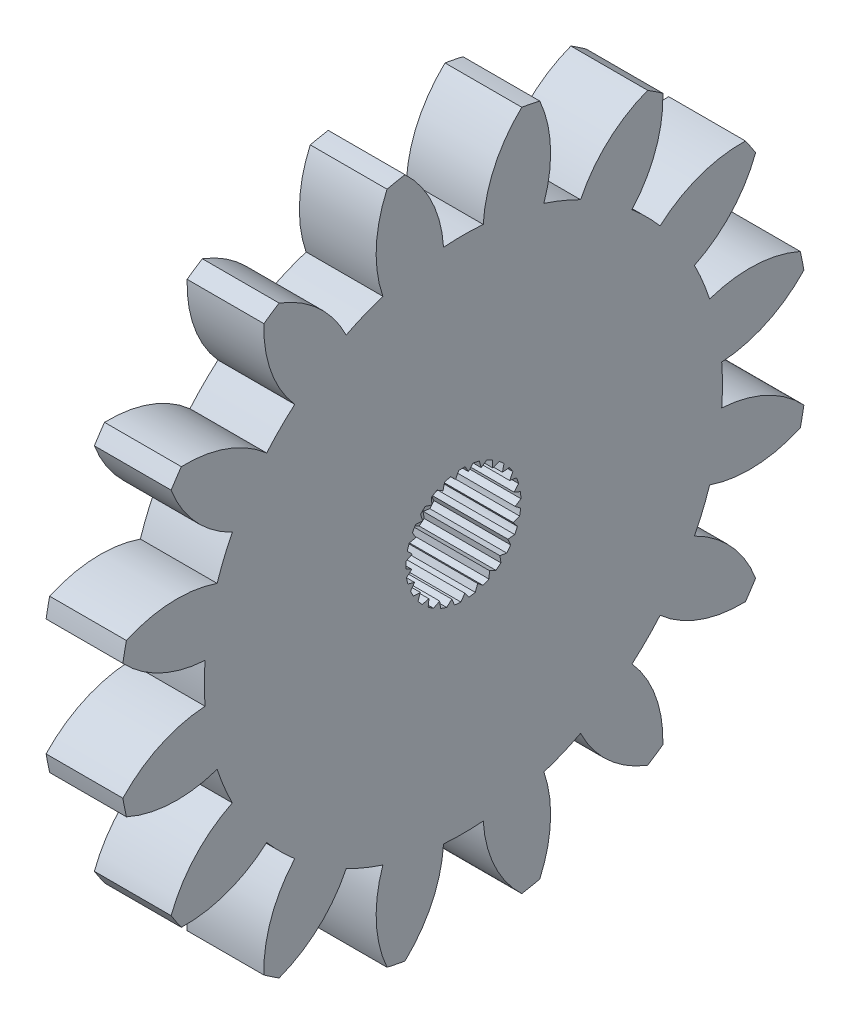
SolidWorks part; units mm, degrees
ref_plane "Plane1" through (0, 0, 0) normal (0, 0, 1) x (1, 0, 0)
ref_plane "Plane2" through (0, 0, 0) normal (0, 1, 0) x (1, 0, 0)
ref_plane "Plane3" through (0, 0, 0) normal (1, 0, 0) x (0, 0, -1)
other "Configuration Table"
sketch "HoldingSke" plane through (0, 0, 0) normal (0, 1, 0) x (1, 0, 0)
  line L0 (0, 0) -> (0.4806, -0.1378)
  line L1 (-15, 0) -> (100, 0) construction
  line L2 (0, 0) -> (-2.1039, 2.3779)
  line L3 (0, 0) -> (-11.863, 4.5341)
  line L4 (0, 0) -> (8.3015, 2.3804)
  line L5 (0, 0) -> (-46.8476, -17.4728)
  line L6 (0, 0) -> (-3.3159, -2.2372)
  line L7 (-2.1039, 2.3779) -> (8.6586, 51.2059)
  line L8 (-76.2, 54.61) -> (-75.2, 54.61)
  line L9 (-71.009, 38.7566) -> (-53.1078, 45.2721)
  line L10 (-76.2, 71.12) -> (104.1128, 71.12)
  line L11 (0, 0) -> (-4, 0)
  line L12 (-76.2, 101.6) -> (-76.133, 101.6)
  line L13 (24.9733, 27.94) -> (52.9518, 28.4284)
  line L14 (24.9733, 27.94) -> (24.9743, 27.94)
  line L15 (24.9733, 27.94) -> (100.4006, 29.5858)
  line L16 (-63.627, -2) -> (-12.827, -2)
  circle A0 centre (0, 0) radius 3
  circle A1 centre (0, 0) radius 13.499
  circle A2 centre (0, 0) radius 37.5
  circle A3 centre (0, 0) radius 3
  dimension "MHD" = 26.998
  dimension "Hub_dia" = 75
  dimension "Bore" = 6
  dimension "MBD" = 6
  dimension "Num_teeth" = 16
  dimension "Pitch" = 0.5
  dimension "Overall_len" = 50
  dimension "Show_teeth" = 16
  dimension "Thickness" = 4
  dimension "OAL" = 50.0001
  dimension "T_dim" = 1
  dimension "Ap" = 20
  dimension "H" = 19.05
  dimension "Pitch_radius" = 180.3128
  dimension "Width" = 4
  dimension "Backlash" = 0.067
  dimension "Addendum_fac" = 1
  dimension "Dedendum_fac" = 1.25
  dimension "Clearance_fac" = 0.25
  dimension "Dedendum_add" = 0.001
  dimension "Module" = 2
sketch "BasProSke" plane through (0, 0, 0) normal (0, 1, 0) x (1, 0, 0)
  line L0 (-10, 0) -> (60, 0) construction
  line L1 (0, 0) -> (0, 18)
  line L2 (0, 0) -> (4, 0)
  line L3 (4, 0) -> (4, 18)
  line L4 (4, 18) -> (0, 18)
  dimension "Thickness" = 4
  dimension "Diameter" = 36
revolve "Base-Revolve" add sketch "BasProSke" angle 360 about L0
sketch "TooCutSke" plane through (0, 0, 0) normal (1, 0, 0) x (0, 0, -1)
  line L1 (0, 0) -> (0, 107) construction
  line L2 (0, 0) -> (-1.6854, 15.911) construction
  line L3 (0, 0) -> (-6.2172, 31.2558) construction
  line L4 (-1.6854, 15.911) -> (-3.1086, 15.6279) construction
  arc A0 (1.0343, 13.4593) -> (-1.0343, 13.4593) centre (0, 0) ccw
  arc A1 (3.0657, 17.7628) -> (-3.0657, 17.7628) centre (0, 0) ccw
  circle A2 centre (0, 0) radius 16 construction
  circle A3 centre (0, 0) radius 15.0351 construction
  arc A4 (-1.0343, 13.4593) -> (-3.0657, 17.7628) centre (-7.4228, 13.075) ccw
  arc A5 (3.0657, 17.7628) -> (1.0343, 13.4593) centre (7.4228, 13.075) ccw
  dimension "Root_dia" = 26.998
  dimension "Overcut_dia" = 36.0508
  dimension "Pitch_dia" = 32
  dimension "Base_dia" = 30.0702
  dimension "Flank_rad" = 6.4
  dimension "Half_ang" = 11.25
  dimension "Half_CT" = 1.451
extrude "ToothCut" cut sketch "TooCutSke" along normal through all
fillet "Breaks" [suppressed] radius 0.04
fillet "RootFillets" [suppressed] radius 0.501
pattern_circular "TeethCuts" count 16 every 22.5 about axis through (-10, 0, 0) along (1, 0, 0) of "ToothCut", "RootFillets", "Breaks"
sketch "HubNeaOneSke" plane through (0, 0, 0) normal (-1, 0, 0) x (0, 0, 1)
  circle A0 centre (0, 0) radius 13.499
  dimension "Diameter" = 26.998
extrude "HubNearOne" [suppressed] add sketch "HubNeaOneSke" along normal blind 46.0001
sketch "HubNeaBotSke" plane through (0, 0, 0) normal (-1, 0, 0) x (0, 0, 1)
  circle A0 centre (0, 0) radius 13.499
  dimension "Diameter" = 26.998
extrude "HubNearBoth" [suppressed] add sketch "HubNeaBotSke" along normal blind 23
ref_plane "FarPln" through (4, 0, 0) normal (1, 0, 0) x (0, 0, -1)
sketch "HubFarSke" plane through (4, 0, 0) normal (1, 0, 0) x (0, 0, -1)
  circle A0 centre (0, 0) radius 13.499
  dimension "Diameter" = 26.998
extrude "HubFar" [suppressed] add sketch "HubFarSke" along normal blind 23
sketch "BorSke" plane through (0, 0, 0) normal (1, 0, 0) x (0, 0, -1)
  circle A0 centre (0, 0) radius 3
  dimension "Diameter" = 6
extrude "Bore" cut sketch "BorSke" along normal mid plane 100.0001
sketch "KeySke" plane through (0, 0, 0) normal (1, 0, 0) x (0, 0, -1)
  line L0 (-1, 0) -> (-1, 4)
  line L1 (-1, 4) -> (1, 4)
  line L2 (1, 4) -> (1, 0)
  line L3 (0, 0) -> (0, 34) construction
  line L4 (-1, 0) -> (1, 0)
  dimension "Offset" = 4
  dimension "Width" = 2
extrude "Keyway" [suppressed] cut sketch "KeySke" along normal mid plane 100.0001
pattern_circular "Keyway2" [suppressed] count 2 every 90 about axis through (-10, 0, 0) along (1, 0, 0)
sketch "Croquis4" plane through (0, 0, 0) normal (-1, 0, 0) x (0, 0, 1)
  line L0 (-0.2665, 2.6868) -> (-0.504, 2.9574)
  line L1 (-0.2665, 2.6868) -> (-0.0868, 2.9987)
  arc A1 (-0.0868, 2.9987) -> (-0.504, 2.9574) centre (0, 0) ccw
  dimension "D1" = 1.1212
  dimension "D2" = 6
  dimension "D3" = 0.36
  dimension "D4" = 1.3009
extrude "Saliente-Extruir2" add sketch "Croquis4" against normal through all
pattern_circular "MatrizC1" count 25 over 360 about axis through (0, 0, 0) along (1, 0, 0) of "Saliente-Extruir2"
sketch "Croquis5" plane through (0, 0, 0) normal (-1, 0, 0) x (0, 0, 1)
  circle A0 centre (0, 0) radius 1.5
  circle A1 centre (0, 0) radius 4
  dimension "D1" = 3
  dimension "D2" = 8
extrude "Saliente-Extruir3" add sketch "Croquis5" along normal blind 2 contours A1 A0
sketch "Croquis6" plane through (-2, 0, 0) normal (-1, 0, 0) x (0, 0, 1)
  circle A0 centre (0, 0) radius 2.85
  dimension "D1" = 5.7
extrude "Cortar-Extruir4" cut sketch "Croquis6" against normal blind 0.8
equation "' \"Module@HoldingSke\" = 6.35"
equation "' \"Num_teeth@HoldingSke\" = 12"
equation "' \"Ap@HoldingSke\" =  20"
equation "' \"Ap@HoldingSke\" = 20"
equation "' \"Width@HoldingSke\" = 0.5 * 25.4"
equation "' \"Hub_dia@HoldingSke\"= 1 * 25.4"
equation "' \"Hub_dia@HoldingSke\" = 1 * 25.4"
equation "' \"Overall_len@HoldingSke\" = 1.0 * 25.4"
equation "' \"Bore@HoldingSke\" = 0.75 * 25.4"
equation "' \"T_dim@HoldingSke\" = 0.1 * 25.4"
equation "' \"Width@KeySke\" = 0.25 * 25.4"
equation "' \"Show_teeth@HoldingSke\" = 13"
equation "' \"Backlash@HoldingSke\" = 0.009 * 25.4"
equation "' \"Addendum_fac@HoldingSke\" = 1.0"
equation "' \"Dedendum_fac@HoldingSke\" = 1.25"
equation "' \"Dedendum_add@HoldingSke\" = 0.00005 * 25.4"
equation "' \"Clearance_fac@HoldingSke\" = 0.25"
equation "\"Pitch@HoldingSke\" = 1 / \"Module@HoldingSke\""
equation "\"Overcut_dia@TooCutSke\" = (\"Num_teeth@HoldingSke\" + 2 * \"Addendum_fac@HoldingSke\") / \"Pitch@HoldingSke\" + 0.002 * 25.4"
equation "\"Pitch_dia@TooCutSke\" = \"Num_teeth@HoldingSke\" / \"Pitch@HoldingSke\""
equation "\"Base_dia@TooCutSke\" = \"Num_teeth@HoldingSke\" / \"Pitch@HoldingSke\" * cos((\"Ap@HoldingSke\"  * 3.14159265 / 180))"
equation "\"Root_dia@TooCutSke\" = (\"Num_teeth@HoldingSke\" + 2) / \"Pitch@HoldingSke\" - 2 * (\"Addendum_fac@HoldingSke\" + \"Dedendum_fac@HoldingSke\") / \"Pitch@HoldingSke\" - \"Dedendum_add@HoldingSke\" * 2"
equation "\"Half_ang@TooCutSke\" = 180 / \"Num_teeth@HoldingSke\""
equation "\"Half_CT@TooCutSke\" = \"Num_teeth@HoldingSke\" / \"Pitch@HoldingSke\" * sin((3.14159265 / 2 / \"Num_teeth@HoldingSke\")) / 2 - 7 * \"Backlash@HoldingSke\" / 4"
equation "\"Flank_rad@TooCutSke\" = \"Num_teeth@HoldingSke\" / \"Pitch@HoldingSke\" / 5"
equation "\"Radius@RootFillets\" = \"Clearance_fac@HoldingSke\" / \"Pitch@HoldingSke\" + \"Dedendum_add@HoldingSke\""
equation "\"Break_rad@Breaks\" = 0.02 / \"Pitch@HoldingSke\""
equation "\"Thickness@HoldingSke\" = \"Width@HoldingSke\""
equation "\"OAL@HoldingSke\" = \"Thickness@HoldingSke\""
equation "\"MHD@HoldingSke\" = (\"Num_teeth@HoldingSke\" + 2) / \"Pitch@HoldingSke\" - 2 * (\"Addendum_fac@HoldingSke\" + \"Dedendum_fac@HoldingSke\")  / \"Pitch@HoldingSke\" - \"Dedendum_add@HoldingSke\" * 2"
equation "\"MBD@HoldingSke\" = (\"Num_teeth@HoldingSke\" + 2) / \"Pitch@HoldingSke\" - 2 * (\"Addendum_fac@HoldingSke\" + \"Dedendum_fac@HoldingSke\")  / \"Pitch@HoldingSke\" - \"Dedendum_add@HoldingSke\" * 2 - 0.002 * 25.4"
equation "\"MHD@HoldingSke\" = ((sgn( \"MHD@HoldingSke\" - \"Hub_dia@HoldingSke\" )-1)*( \"MHD@HoldingSke\" - \"Hub_dia@HoldingSke\" ))/-2+ \"Hub_dia@HoldingSke\""
equation "\"MBD@HoldingSke\" = ((sgn( \"MBD@HoldingSke\" - \"Bore@HoldingSke\" )-1)*( \"MBD@HoldingSke\" - \"Bore@HoldingSke\" ))/-2+ \"Bore@HoldingSke\""
equation "\"OAL@HoldingSke\" = ((sgn( \"OAL@HoldingSke\" - \"Overall_len@HoldingSke\" )+1)*( \"OAL@HoldingSke\" - \"Overall_len@HoldingSke\" ))/2 + \"Overall_len@HoldingSke\" + 0.000002 * 25.4"
equation "\"Num_teeth@TeethCuts\" = int( \"Show_teeth@HoldingSke\" ) + 1"
equation "\"Num_teeth@TeethCuts\" = ((sgn( \"Num_teeth@TeethCuts\" - \"Num_teeth@HoldingSke\" )-1)*( \"Num_teeth@TeethCuts\" - \"Num_teeth@HoldingSke\" ))/-2+ \"Num_teeth@HoldingSke\""
equation "\"Num_teeth@TeethCuts\" = ((sgn( \"Num_teeth@TeethCuts\" - 2.0)+1)*( \"Num_teeth@TeethCuts\" - 2.0))/2 +2.0"
equation "\"Angle@TeethCuts\" = 360.0 / \"Num_teeth@HoldingSke\""
equation "\"Diameter@BasProSke\" = (\"Num_teeth@HoldingSke\" + 2 * \"Addendum_fac@HoldingSke\") / \"Pitch@HoldingSke\""
equation "\"Thickness@BasProSke\"  = \"Thickness@HoldingSke\""
equation "' \"Fillet_rad@BasProSke\" =  \"Thickness@HoldingSke\" * 0.05"
equation "' \"Fillet_rad@BasProSke\" = \"Thickness@HoldingSke\" * 0.05"
equation "\"MHD@HoldingSke\" = ((sgn( \"MHD@HoldingSke\" - \"Root_dia@TooCutSke\" )-1)*( \"MHD@HoldingSke\" - \"Root_dia@TooCutSke\" ))/-2+ \"Root_dia@TooCutSke\""
equation "\"Diameter@HubNeaOneSke\" = \"MHD@HoldingSke\""
equation "\"Length@HubNearOne\" = \"OAL@HoldingSke\" - \"Thickness@BasProSke\""
equation "\"Diameter@HubNeaBotSke\" = \"MHD@HoldingSke\""
equation "\"Length@HubNearBoth\" = ( \"OAL@HoldingSke\" - \"Thickness@BasProSke\" ) / 2.0"
equation "\"Thickness@FarPln\" = \"Thickness@BasProSke\""
equation "\"Diameter@HubFarSke\" = \"MHD@HoldingSke\""
equation "\"Length@HubFar\" = ( \"OAL@HoldingSke\" - \"Thickness@BasProSke\" ) / 2.0"
equation "\"Diameter@BorSke\" = \"MBD@HoldingSke\""
equation "\"D1@Bore\" = \"OAL@HoldingSke\" * 2.0"
equation "\"D1@Keyway\" = \"OAL@HoldingSke\" * 2.0"
equation "\"Offset@KeySke\" = \"T_dim@HoldingSke\" + \"MBD@HoldingSke\" / 2.0"
